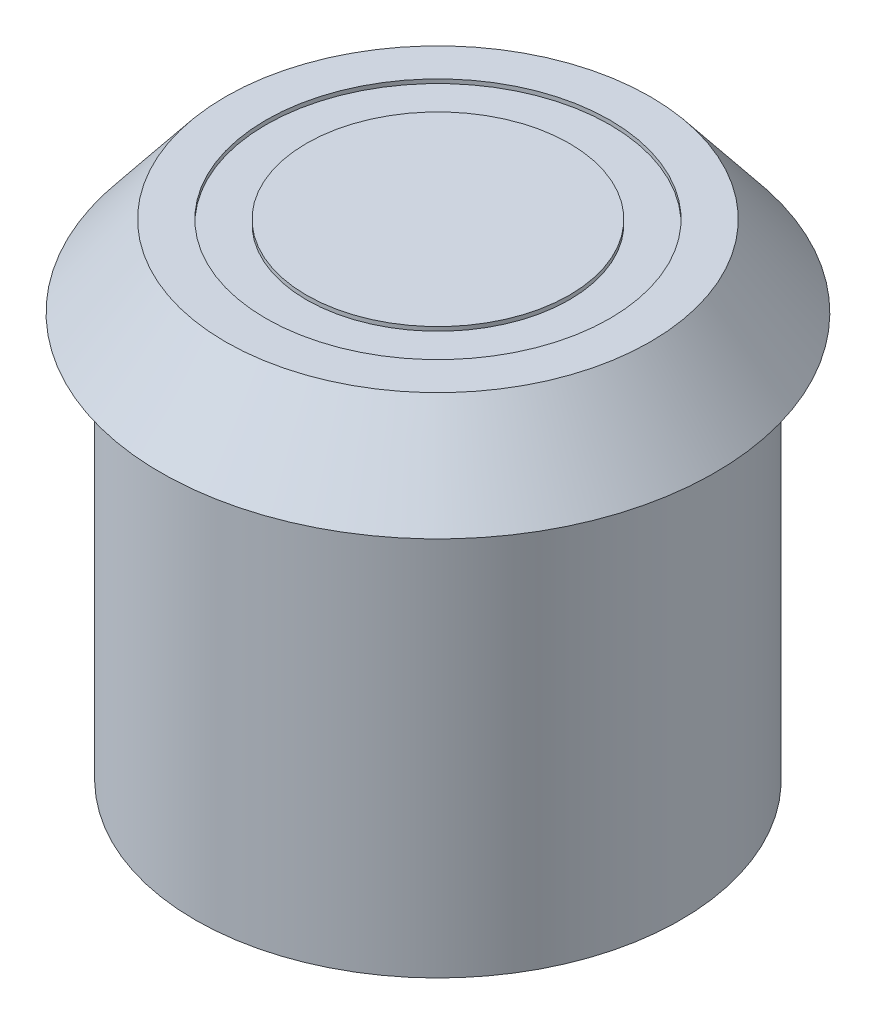
SolidWorks part; units mm, degrees
ref_plane "Plan de face" through (0, 0, 0) normal (0, 0, 1) x (1, 0, 0)
ref_plane "Plan de dessus" through (0, 0, 0) normal (0, 1, 0) x (1, 0, 0)
ref_plane "Plan de droite" through (0, 0, 0) normal (1, 0, 0) x (0, 0, -1)
sketch "Esquisse1" plane through (0, 0, 0) normal (0, 1, 0) x (1, 0, 0)
  circle A0 centre (0, 0) radius 6
  dimension "D1" = 12
extrude "Boss.-Extru.1" add sketch "Esquisse1" against normal blind 10
sketch "Esquisse3" plane through (0, 0, 0) normal (1, 0, 0) x (0, 0, -1)
  line L0 (0, 0) -> (0, 2)
  line L1 (0, 2) -> (5.25, 2)
  line L2 (5.25, 2) -> (6.85, 0)
  line L3 (6.85, 0) -> (0, 0)
  line L4 (0, 0) -> (0, 2.7474) construction
  dimension "D1" = 13.7
  dimension "D2" = 2
  dimension "D3" = 10.5
revolve "Révolution1" add sketch "Esquisse3" angle 360 about L4
sketch "Esquisse4" plane through (0, 2, 0) normal (0, 1, 0) x (1, 0, 0)
  circle A0 centre (0, 0) radius 4.25
  circle A1 centre (0, 0) radius 3.25
  dimension "D1" = 6.5
  dimension "D2" = 8.5
extrude "Enlèv. mat.-Extru.1" cut sketch "Esquisse4" against normal blind 0.1
